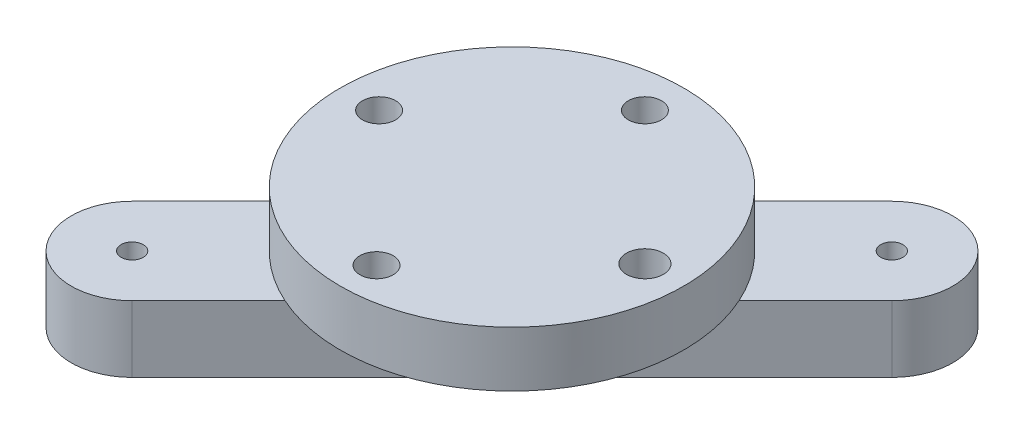
SolidWorks part; units mm, degrees
ref_plane "Front Plane" through (0, 0, 0) normal (0, 0, 1) x (1, 0, 0)
ref_plane "Top Plane" through (0, 0, 0) normal (0, 1, 0) x (1, 0, 0)
ref_plane "Right Plane" through (0, 0, 0) normal (1, 0, 0) x (0, 0, -1)
sketch "Sketch1" plane through (0, 0, 0) normal (0, 1, 0) x (1, 0, 0)
  circle A0 centre (0, 0) radius 31
extrude "Boss-Extrude1" add sketch "Sketch1" along normal blind 10 contours A0
sketch "Sketch3" plane through (0, 0, 0) normal (0, 1, 0) x (1, 0, 0)
  circle A0 centre (0, 24) radius 5
  circle A1 centre (0, 0) radius 31 construction
  dimension "D1" = 24
extrude "Cut-Extrude1" cut sketch "Sketch3" along normal blind 4 contours A0
sketch "Sketch5" plane through (0, 0, 0) normal (0, 1, 0) x (1, 0, 0)
  circle A0 centre (-24, 0) radius 5
  circle A1 centre (24, 0) radius 5
  circle A2 centre (0, -24) radius 5
  dimension "D1" = 24
  dimension "D4" = 48
  dimension "D2" = 24
  dimension "D3" = 24
extrude "Cut-Extrude2" cut sketch "Sketch5" along normal blind 4
sketch "Sketch6" plane through (0, 0, 0) normal (0, 1, 0) x (1, 0, 0)
  circle A0 centre (0, -24.4603) radius 3
  circle A2 centre (-24, 0) radius 3
  circle A3 centre (24, 0) radius 3.3296
  circle A4 centre (0, 24) radius 3
  dimension "D1" = 24
  dimension "D2" = 24
  dimension "D3" = 24
extrude "Cut-Extrude3" cut sketch "Sketch6" along normal blind 10
sketch "Sketch10" plane through (0, 0, 0) normal (0, 1, 0) x (1, 0, 0)
  line L0 (-34.2947, -34.2947) -> (34.2947, 34.2947) construction
  line L1 (-42.0729, -26.5165) -> (26.5165, 42.0729)
  line L2 (-26.5165, -42.0729) -> (42.0729, 26.5165)
  arc A0 (-42.0729, -26.5165) -> (-26.5165, -42.0729) centre (-34.2947, -34.2947) ccw
  arc A1 (42.0729, 26.5165) -> (26.5165, 42.0729) centre (34.2947, 34.2947) ccw
  circle A2 centre (34.2947, 34.2947) radius 2
  circle A3 centre (-34.2947, -34.2947) radius 2
  point P2 (0, 0)
  point P12 (0, 0)
extrude "Boss-Extrude5" add sketch "Sketch10" against normal blind 12
